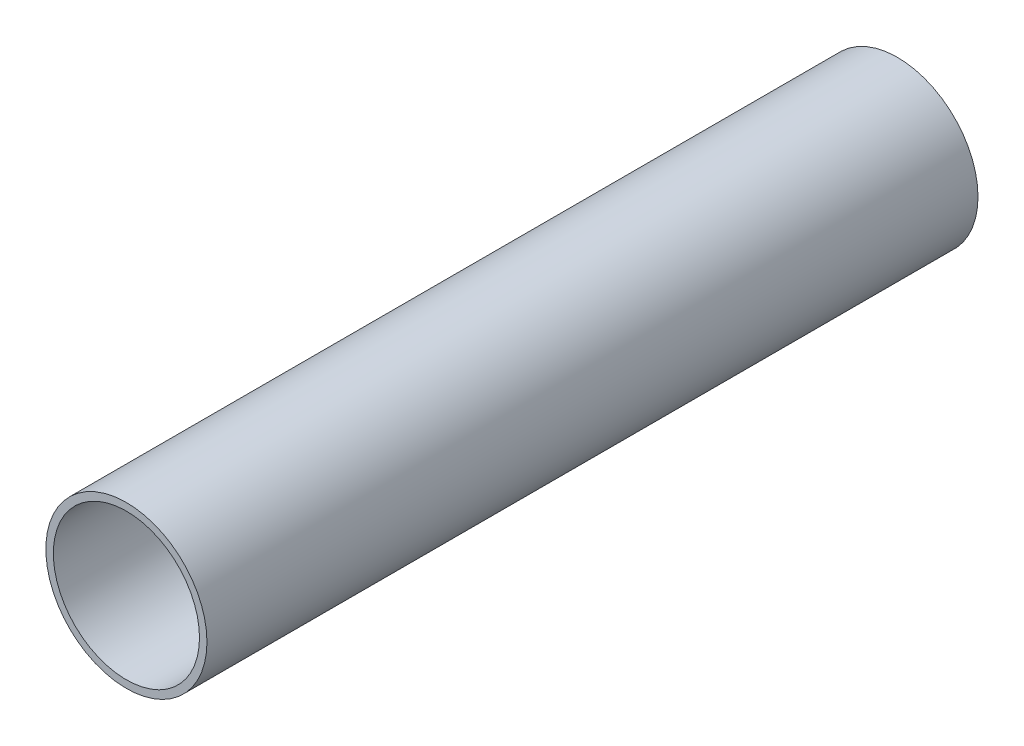
SolidWorks part; units mm, degrees
material "铜"
ref_plane "前视基准面" through (0, 0, 0) normal (0, 0, 1) x (1, 0, 0)
ref_plane "上视基准面" through (0, 0, 0) normal (0, 1, 0) x (1, 0, 0)
ref_plane "右视基准面" through (0, 0, 0) normal (1, 0, 0) x (0, 0, -1)
sketch "草图1" plane through (0, 0, 0) normal (0, 0, 1) x (1, 0, 0)
  circle A0 centre (0, 0) radius 12.7
  circle A1 centre (0, 0) radius 14
  dimension "D1" = 28
  dimension "D2" = 1.3
extrude "凸台-拉伸1" add sketch "草图1" along normal blind 134
